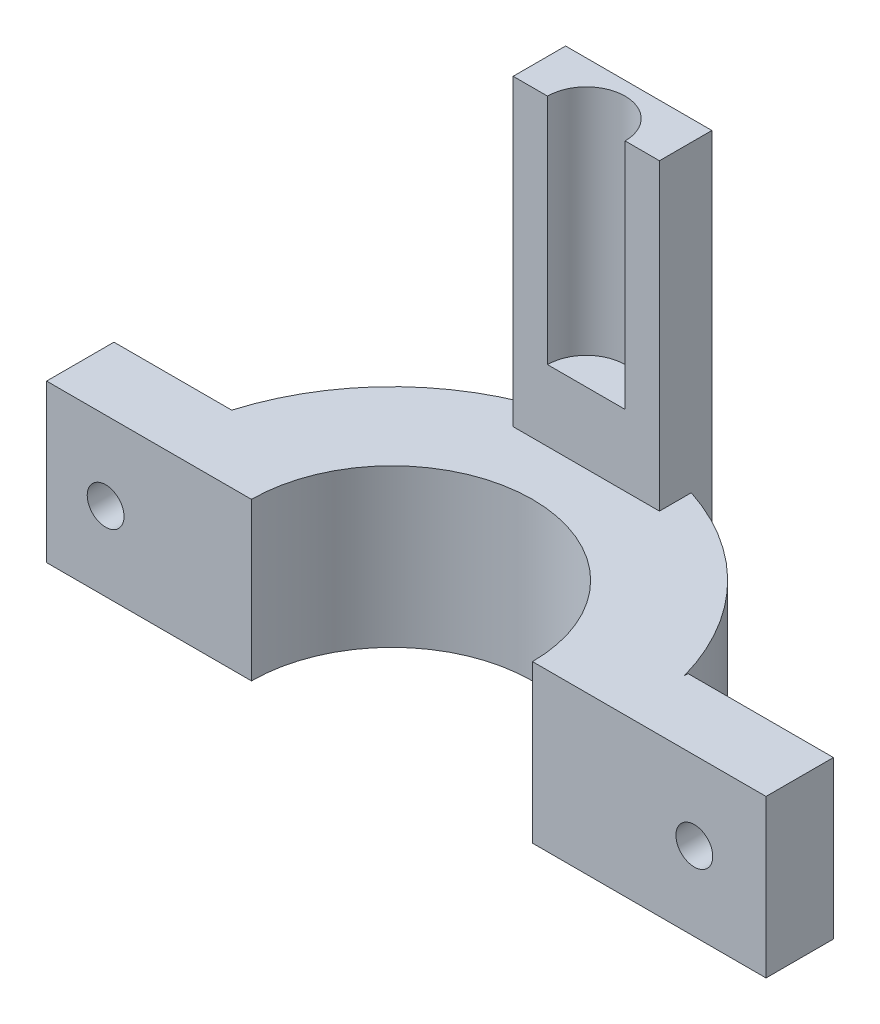
SolidWorks part; units mm, degrees
ref_plane "前基準面" through (0, 0, 0) normal (0, 0, 1) x (1, 0, 0)
ref_plane "上基準面" through (0, 0, 0) normal (0, 1, 0) x (1, 0, 0)
ref_plane "右基準面" through (0, 0, 0) normal (1, 0, 0) x (0, 0, -1)
sketch "草圖1" plane through (0, 0, 0) normal (0, 1, 0) x (1, 0, 0)
  line L1 (-14.255, 7) -> (14.255, 7)
  line L2 (-14.255, 7) -> (-14.255, -7)
  line L3 (-14.255, -7) -> (14.255, -7)
  line L4 (14.255, 7) -> (14.255, -7)
  line L5 (-14.255, 7) -> (14.255, -7) construction
  line L6 (-14.255, -7) -> (14.255, 7) construction
  point P0 (0, 0)
  dimension "D1" = 14
  dimension "D2" = 28.51
extrude "伸長-薄件1" add sketch "草圖1" along normal blind 12.25 thin thin type one direction wall 10
sketch "草圖2" plane through (0, 12.25, 0) normal (0, 1, 0) x (1, 0, 0)
  line L0 (-1014.255, 0) -> (48985.745, 0) construction
  line L1 (-14.255, 7) -> (-14.255, -7) construction
  line L2 (-19.255, -988.4004) -> (-19.255, 49011.5996) construction
  line L3 (-24.255, 17) -> (-19.255, 17) construction
  line L4 (-24.255, 17) -> (-24.255, 11.5996) construction
  line L5 (-24.255, 11.5996) -> (-19.255, 11.5996) construction
  line L6 (-19.255, 17) -> (-19.255, 11.5996) construction
  line L7 (24.255, 17) -> (19.255, 17) construction
  line L8 (24.255, 17) -> (24.255, 12.4477) construction
  line L9 (24.255, 12.4477) -> (19.255, 12.4477) construction
  line L10 (19.255, 17) -> (19.255, 12.4477) construction
  line L11 (19.255, -987.5523) -> (19.255, 49012.4477) construction
  circle A0 centre (-19.255, 0) radius 1.91
  circle A1 centre (19.255, 0) radius 1.91
  point P5 (-14.255, 0)
  dimension "D3" = 3.82
  dimension "D4" = 3.82
  dimension "D1" = 5
  dimension "D2" = 5
extrude "除料-伸長1" cut sketch "草圖2" against normal through all
sketch "草圖4" plane through (0, 0, 0) normal (0, -1, 0) x (1, 0, 0)
  line L0 (-1000, 0) -> (49000, 0) construction
  line L1 (24.255, 17) -> (24.255, -17) construction
  line L2 (11.255, 6.955) -> (24.255, 6.955)
  line L3 (11.255, 6.955) -> (11.255, -6.955)
  line L4 (11.255, -6.955) -> (24.255, -6.955)
  line L5 (24.255, 6.955) -> (24.255, -6.955)
  line L6 (11.255, 6.955) -> (24.255, -6.955) construction
  line L7 (11.255, -6.955) -> (24.255, 6.955) construction
  point P1 (17.755, 0)
  dimension "D1" = 13.91
  dimension "D2" = 13
extrude "填料-伸長1" add sketch "草圖4" along normal blind 74.82
sketch "草圖5" plane through (11.255, 0, 0) normal (-1, 0, 0) x (0, 0, 1)
  line L0 (6.955, -74.82) -> (6.955, 0) construction
  line L1 (-6.955, -74.82) -> (6.955, -74.82)
  line L2 (-6.955, -74.82) -> (-6.955, -58.59)
  line L3 (-6.955, -58.59) -> (6.955, -58.59)
  line L4 (6.955, -74.82) -> (6.955, -58.59)
  dimension "D1" = 16.23
extrude "填料-伸長2" add sketch "草圖5" along normal blind 15
sketch "草圖7" plane through (3.6267, -74.82, 0) normal (0, -1, 0) x (1, 0, 0)
  circle A0 centre (-30.9782, 0) radius 14.5
  dimension "D1" = 29
extrude "伸長-薄件2" add sketch "草圖7" against normal blind 16.23 thin
ref_plane "平面1" through (-60, 0, 0) normal (1, 0, 0) x (0, 0, -1)
sketch "草圖12" plane through (0, 0, -6.955) normal (0, 0, -1) x (-1, 0, 0)
  line L0 (-996.255, -66.705) -> (49003.745, -66.705) construction
  line L1 (3.745, -74.82) -> (3.745, -58.59) construction
  line L2 (-3.755, -1058.59) -> (-3.755, 48941.41) construction
  line L3 (3.745, -58.59) -> (-11.255, -58.59) construction
  circle A0 centre (-3.8567, -66.705) radius 1.9
  point P5 (3.745, -66.705)
  point P10 (-3.755, -58.59)
  dimension "D1" = 3.8
extrude "除料-伸長4" cut sketch "草圖12" against normal through all
ref_plane "平面2" through (-55, 0, 0) normal (1, 0, 0) x (0, 0, -1)
sketch "草圖13" plane through (-55, 0, 0) normal (1, 0, 0) x (0, 0, -1)
  line L1 (6.955, -58.59) -> (-6.955, -58.59)
  line L2 (6.955, -58.59) -> (6.955, -74.82)
  line L3 (6.955, -74.82) -> (-6.955, -74.82)
  line L4 (-6.955, -58.59) -> (-6.955, -74.82)
extrude "填料-伸長3" add sketch "草圖13" along normal blind 10 and the other way blind 8
sketch "草圖14" plane through (0, 0, -6.955) normal (0, 0, -1) x (-1, 0, 0)
  line L0 (-949.1564, -66.705) -> (49050.8436, -66.705) construction
  line L1 (50.8436, -58.59) -> (50.8436, -74.82) construction
  line L2 (56.9218, -1058.59) -> (56.9218, 48941.41) construction
  line L3 (63, -58.59) -> (50.8436, -58.59) construction
  circle A0 centre (56.908, -66.705) radius 1.9
  point P5 (50.8436, -66.705)
  point P10 (56.9218, -58.59)
  dimension "D1" = 3.8
extrude "除料-伸長5" cut sketch "草圖14" against normal through all
sketch "草圖16" plane through (0, 12.25, 0) normal (0, 1, 0) x (1, 0, 0)
  line L0 (-63, 6.955) -> (-63, -6.955) construction
  line L1 (-63, 0) -> (27.7094, 0)
  line L2 (-63, 0) -> (-63, -28.9551)
  line L3 (-63, -28.9551) -> (27.7094, -28.9551)
  line L4 (27.7094, 0) -> (27.7094, -28.9551)
extrude "除料-伸長7" cut sketch "草圖16" against normal through all
sketch "草圖17" plane through (11.255, 0, 0) normal (-1, 0, 0) x (0, 0, 1)
  line L1 (0, -58.59) -> (-20.2305, -58.59)
  line L2 (0, -58.59) -> (0, 22.1336)
  line L3 (0, 22.1336) -> (-20.2305, 22.1336)
  line L4 (-20.2305, -58.59) -> (-20.2305, 22.1336)
sketch "草圖18" plane through (0, 0, 0) normal (0, 0, 1) x (1, 0, 0)
  line L0 (11.255, -58.59) -> (11.255, 22.1336) construction
  line L1 (24.255, -74.82) -> (11.255, -74.82)
  line L2 (24.255, -74.82) -> (24.255, 18.2609)
  line L3 (24.255, 18.2609) -> (11.255, 18.2609)
  line L4 (11.255, -74.82) -> (11.255, 18.2609)
extrude "除料-伸長10" cut sketch "草圖18" against normal blind 27
extrude "除料-伸長11" cut sketch "草圖17" against normal blind 27 and the other way blind 57
ref_plane "平面3" through (0, 0, -30) normal (0, 0, 1) x (1, 0, 0)
sketch "草圖21" plane through (0, 0, -30) normal (0, 0, 1) x (1, 0, 0)
  line L0 (-27.2943, -1058.59) -> (-27.2943, 48941.41) construction
  line L1 (-3.745, -58.59) -> (-50.8436, -58.59) construction
  line L2 (-3.745, -58.59) -> (-3.745, -74.82) construction
  line L3 (-19.745, -27.2694) -> (-34.8436, -27.2694)
  line L4 (-19.745, -27.2694) -> (-19.745, -69.7694)
  line L5 (-19.745, -69.7694) -> (-34.8436, -69.7694)
  line L6 (-34.8436, -27.2694) -> (-34.8436, -69.7694)
  line L7 (-50.8436, -58.59) -> (-50.8436, -74.82) construction
  point P5 (-27.2943, -58.59)
  dimension "D1" = 16
  dimension "D2" = 16
  dimension "D3" = 42.5
extrude "填料-伸長6" add sketch "草圖21" along normal blind 10
sketch "草圖22" plane through (0, -27.2694, 0) normal (0, 1, 0) x (1, 0, 0)
  line L0 (-34.8436, 20) -> (-19.745, 20) construction
  circle A0 centre (-27.2943, 20) radius 4.005
  dimension "D1" = 8.01
extrude "除料-伸長12" cut sketch "草圖22" against normal blind 24
sketch "草圖23" plane through (0, -27.2694, 0) normal (0, 1, 0) x (1, 0, 0)
  line L0 (-19.745, 20) -> (-19.745, 30) construction
  line L1 (-34.8436, 30) -> (-19.745, 30)
  line L2 (-34.8436, 30) -> (-34.8436, 25.4125)
  line L3 (-34.8436, 25.4125) -> (-19.745, 25.4125)
  line L4 (-19.745, 30) -> (-19.745, 25.4125)
extrude "除料-伸長13" cut sketch "草圖23" against normal through all
